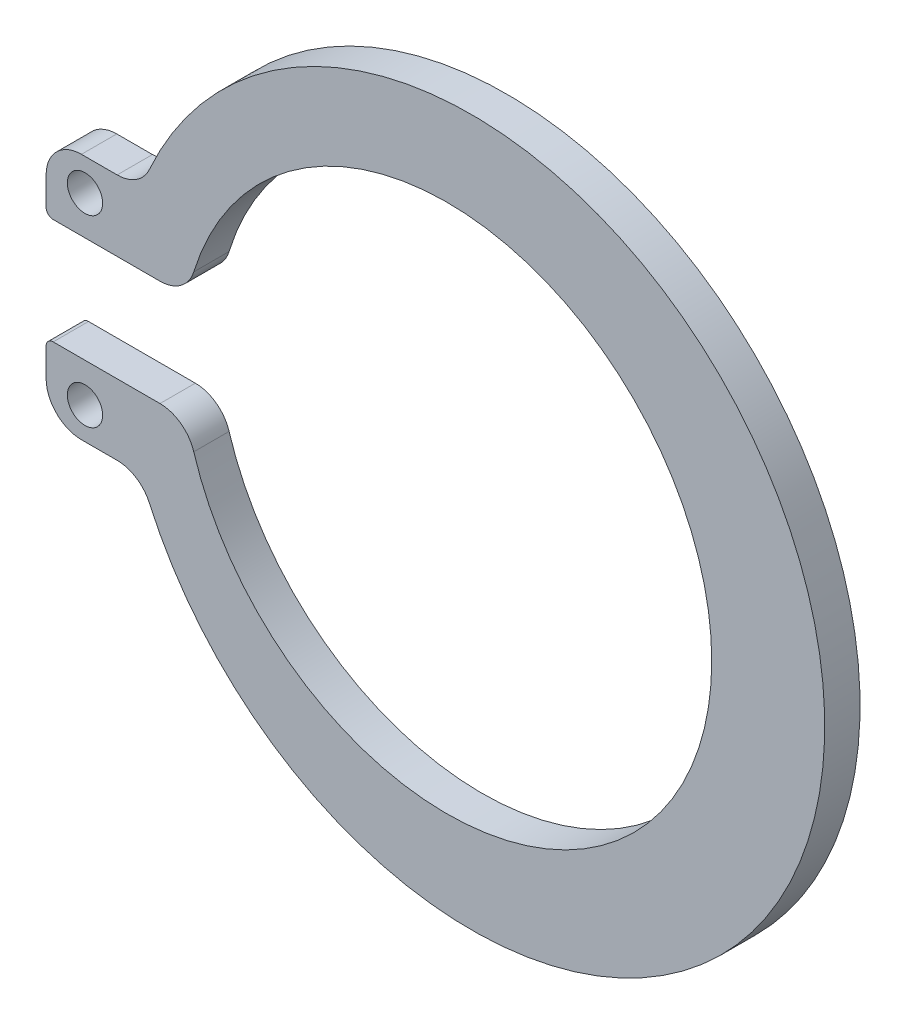
SolidWorks part; units mm, degrees
ref_plane "Front Plane" through (0, 0, 0) normal (0, 0, 1) x (1, 0, 0)
ref_plane "Top Plane" through (0, 0, 0) normal (0, 1, 0) x (1, 0, 0)
ref_plane "Right Plane" through (0, 0, 0) normal (1, 0, 0) x (0, 0, -1)
sketch "Sketch1" plane through (0, 0, 0) normal (0, 0, 1) x (1, 0, 0)
  line L2 (0, 0) -> (-6.4634, 0) construction
  line L4 (-3.6742, 0.75) -> (-5.6742, 0.75)
  line L6 (-4.3337, 1.75) -> (-5.6742, 1.75)
  line L7 (-5.6742, 0.75) -> (-5.6742, 1.75)
  line L8 (-3.6742, -0.75) -> (-5.6742, -0.75)
  line L10 (-4.3337, -1.75) -> (-5.6742, -1.75)
  line L11 (-5.6742, -0.75) -> (-5.6742, -1.75)
  arc A0 (-3.6742, -0.75) -> (-3.6742, 0.75) centre (0, 0) ccw
  arc A1 (-4.3337, -1.75) -> (-4.3337, 1.75) centre (0.35, 0) ccw
  dimension "D1" = 7.5
  dimension "D4" = 10
  dimension "D2" = 0.35
  dimension "D3" = 1.5
  dimension "D5" = 2
  dimension "D6" = 1
extrude "Boss-Extrude1" add sketch "Sketch1" along normal blind 0.5
fillet "Fillet1" radius 0.5 6 edges at (-4.3337, -1.75, 0.25) (-3.6742, -0.75, 0.25) (-3.6742, 0.75, 0.25) (-4.3337, 1.75, 0.25) (-5.6742, -1.75, 0.25) (-5.6742, 1.75, 0.25)
fillet "Fillet2" radius 0.1 2 edges at (-5.6742, 0.75, 0.25) (-5.6742, -0.75, 0.25)
sketch "Sketch2" plane through (0, 0, 0.5) normal (0, 0, 1) x (1, 0, 0)
  line L0 (-5.6742, 1.25) -> (-5.6742, 0.85) construction
  line L1 (-4.062, -0.75) -> (-5.5742, -0.75) construction
  line L2 (-7.3693, 0) -> (0, 0) construction
  circle A0 centre (-5.1242, 1.3) radius 0.25
  circle A1 centre (-5.1242, -1.3) radius 0.25
  dimension "D3" = 0.5
  dimension "D1" = 0.55
  dimension "D2" = 0.55
extrude "Cut-Extrude1" cut sketch "Sketch2" against normal up to next
